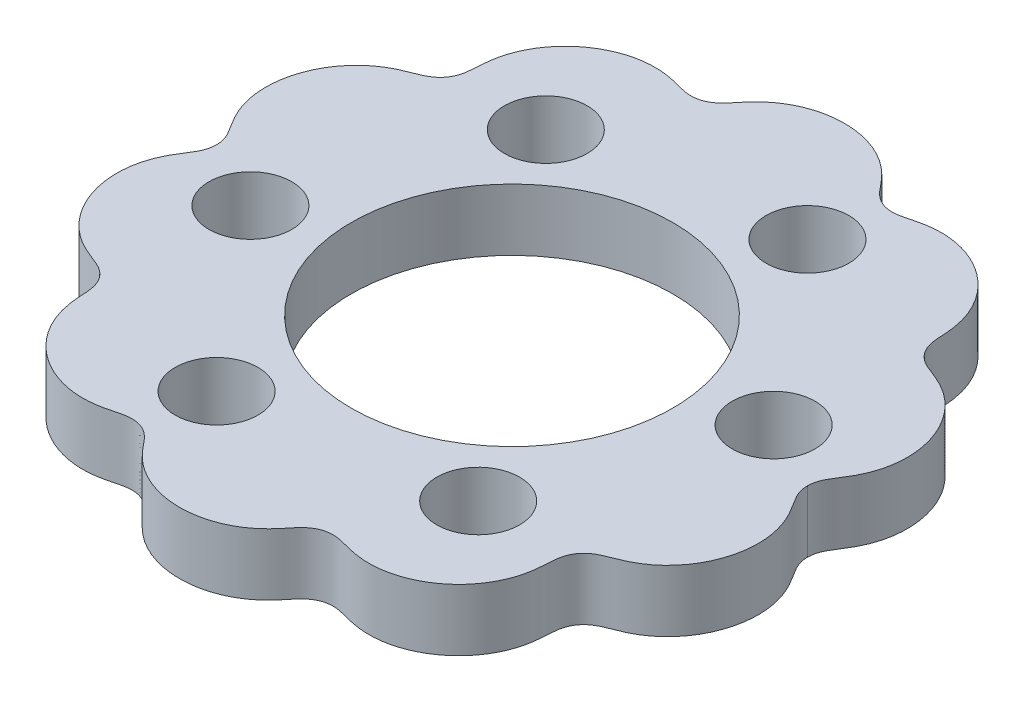
SolidWorks part; units mm, degrees
ref_plane "Front Plane" through (0, 0, 0) normal (0, 0, 1) x (1, 0, 0)
ref_plane "Top Plane" through (0, 0, 0) normal (0, 1, 0) x (1, 0, 0)
ref_plane "Right Plane" through (0, 0, 0) normal (1, 0, 0) x (0, 0, -1)
sketch "Sketch1" plane through (0, 0, 0) normal (0, 1, 0) x (1, 0, 0)
  spline S0 degree 4 poles (25.7906, 7.5343) (25.8788, 7.1133) (25.9899, 6.258) (25.9622, 5.173) (25.6669, 3.909) (25.2966, 3.0278) (25.0022, 2.4855) (24.7411, 2.0653) (24.5631, 1.7918) (24.4128, 1.5559) (24.2753, 1.3229) (24.1728, 1.1289) (24.0852, 0.9325) (24.0168, 0.7401) (23.9736, 0.5903) (23.9409, 0.4443) (23.918, 0.3017) (23.9061, 0.188) (23.9012, 0.082) (23.8998, 0.0096) (23.9001, -0.0378) (23.9031, -0.1354) (23.9124, -0.2583) (23.931, -0.3897) (23.9595, -0.5322) (23.992, -0.6548) (24.033, -0.7865) (24.0838, -0.9249) (24.1521, -1.083) (24.2429, -1.2629) (24.3447, -1.4425) (24.4552, -1.6225) (24.5717, -1.8045) (24.7183, -2.0313) (24.8914, -2.3053) (25.0875, -2.6402) (25.2934, -3.0428) (25.5234, -3.5754) (25.7435, -4.2491) (25.909, -5.0602) (25.989, -6.24) (25.8643, -7.4222) (25.5418, -8.5683) (25.0323, -9.6423) (24.5159, -10.4451) (23.8988, -11.1736) (23.1893, -11.8124) (22.5069, -12.2735) (21.8941, -12.5927) (21.3804, -12.8129) (20.9812, -12.967) (20.5083, -13.1497) (20.0028, -13.3924) (19.5163, -13.7704) (19.1071, -14.3429) (18.9044, -14.9387) (18.8377, -15.5108) (18.8117, -16.0408) (18.7845, -16.4899) (18.7247, -17.0578) (18.5966, -17.7393) (18.287, -18.7429) (17.6345, -19.995) (16.5677, -21.2689) (15.0187, -22.3804) (13.232, -23.0712) (11.6863, -23.2335) (10.5209, -23.1072) (9.745, -22.9271) (9.3314, -22.8175) (8.8415, -22.6876) (8.2891, -22.5904) (7.675, -22.6156) (7.014, -22.8425) (6.5078, -23.2036) (6.1238, -23.6204) (5.7973, -24.0261) (5.517, -24.3664) (4.9887, -24.958) (4.1217, -25.7163) (2.8002, -26.4589) (0.9866, -26.9323) (-0.8925, -26.9446) (-2.4927, -26.549) (-3.7586, -25.9235) (-4.6012, -25.2962) (-5.1069, -24.8217) (-5.4903, -24.3984) (-5.7768, -24.0514) (-6.1092, -23.6377) (-6.4971, -23.212) (-7.008, -22.8447) (-7.6734, -22.6157) (-8.2891, -22.5904) (-8.8414, -22.6876) (-9.3314, -22.8175) (-9.745, -22.9271) (-10.5209, -23.1072) (-11.6863, -23.2335) (-13.232, -23.0712) (-15.0187, -22.3804) (-16.5677, -21.2689) (-17.6345, -19.995) (-18.287, -18.7429) (-18.5966, -17.7393) (-18.7247, -17.0578) (-18.7845, -16.4899) (-18.8117, -16.0408) (-18.8377, -15.5108) (-18.9044, -14.9387) (-19.1071, -14.3429) (-19.5163, -13.7704) (-20.0028, -13.3924) (-20.5083, -13.1497) (-20.9812, -12.967) (-21.3804, -12.8129) (-21.8941, -12.5927) (-22.5069, -12.2735) (-23.1893, -11.8124) (-23.8988, -11.1736) (-24.5159, -10.4451) (-25.0323, -9.6423) (-25.5418, -8.5683) (-25.8643, -7.4222) (-25.989, -6.24) (-25.909, -5.0602) (-25.7435, -4.2491) (-25.5234, -3.5754) (-25.2934, -3.0428) (-25.0875, -2.6402) (-24.8914, -2.3053) (-24.7183, -2.0313) (-24.5717, -1.8045) (-24.4552, -1.6225) (-24.3447, -1.4425) (-24.2429, -1.2629) (-24.1521, -1.083) (-24.0838, -0.9249) (-24.033, -0.7865) (-23.992, -0.6548) (-23.9595, -0.5322) (-23.931, -0.3897) (-23.9124, -0.2583) (-23.9031, -0.1354) (-23.9001, -0.0378) (-23.8998, 0.0096) (-23.9012, 0.082) (-23.9061, 0.188) (-23.918, 0.3017) (-23.9409, 0.4443) (-23.9736, 0.5903) (-24.0168, 0.7401) (-24.0852, 0.9325) (-24.1918, 1.1715) (-24.3429, 1.4455) (-24.5376, 1.7528) (-24.7411, 2.0653) (-25.0022, 2.4855) (-25.2966, 3.0278) (-25.6669, 3.909) (-25.9622, 5.173) (-25.9899, 6.258) (-25.8788, 7.1133) (-25.7906, 7.5343) knots 0 0 0 0 0 0.016557 0.033114 0.041392 0.04967 0.053259 0.056848 0.060437 0.062231 0.064026 0.067263 0.068881 0.0705 0.071881 0.073262 0.074643 0.076024 0.076447 0.07687 0.077627 0.078384 0.079897 0.081411 0.082924 0.083871 0.084817 0.08671 0.088602 0.090495 0.092574 0.094654 0.096734 0.098813 0.102972 0.107132 0.111671 0.11621 0.125289 0.134368 0.143447 0.161605 0.170766 0.179928 0.18909 0.198252 0.207413 0.216574 0.220692 0.22481 0.228927 0.233045 0.240218 0.246328 0.252328 0.259785 0.264113 0.268441 0.27277 0.277098 0.286094 0.29509 0.313082 0.331073 0.349394 0.367716 0.386036 0.390153 0.39427 0.398387 0.402504 0.409677 0.415786 0.421726 0.429063 0.433304 0.437545 0.441787 0.446028 0.463838 0.481648 0.499458 0.517452 0.535446 0.544443 0.55344 0.557769 0.562098 0.566426 0.570755 0.578213 0.584214 0.590323 0.597496 0.601613 0.60573 0.609847 0.613964 0.632284 0.650606 0.668927 0.686918 0.70491 0.713906 0.722902 0.72723 0.731559 0.735887 0.740215 0.747672 0.753672 0.759782 0.766955 0.771073 0.77519 0.779308 0.783426 0.792587 0.801748 0.81091 0.820072 0.829234 0.838395 0.856553 0.865632 0.874711 0.88379 0.888329 0.892868 0.897028 0.901187 0.903266 0.905346 0.907426 0.909505 0.911398 0.91329 0.915183 0.916129 0.917076 0.918589 0.920103 0.921616 0.922373 0.92313 0.923553 0.923976 0.925357 0.926738 0.928119 0.9295 0.931119 0.932737 0.935974 0.939563 0.943152 0.946741 0.95033 0.958608 0.966886 0.983443 1 1 1 1 1 construction
  spline S1 degree 4 poles (23.9, 0) (23.9, -0.0166) (23.9004, -0.0497) (23.9031, -0.1354) (23.9124, -0.2583) (23.931, -0.3897) (23.9595, -0.5322) (23.992, -0.6548) (24.033, -0.7865) (24.0838, -0.9249) (24.1521, -1.083) (24.2429, -1.2629) (24.3447, -1.4425) (24.4552, -1.6225) (24.5717, -1.8045) (24.7183, -2.0313) (24.8914, -2.3053) (25.0875, -2.6402) (25.2934, -3.0428) (25.5234, -3.5754) (25.7435, -4.2491) (25.909, -5.0602) (25.989, -6.24) (25.8643, -7.4222) (25.5418, -8.5683) (25.0323, -9.6423) (24.5159, -10.4451) (23.8988, -11.1736) (23.1893, -11.8124) (22.5069, -12.2735) (21.8941, -12.5927) (21.3804, -12.8129) (20.9812, -12.967) (20.5083, -13.1497) (20.0028, -13.3924) (19.5163, -13.7704) (19.1071, -14.3429) (18.9044, -14.9387) (18.8377, -15.5108) (18.8117, -16.0408) (18.7845, -16.4899) (18.7247, -17.0578) (18.5966, -17.7393) (18.287, -18.7429) (17.6345, -19.995) (16.5677, -21.2689) (15.0187, -22.3804) (13.232, -23.0712) (11.6863, -23.2335) (10.5209, -23.1072) (9.745, -22.9271) (9.3314, -22.8175) (8.8415, -22.6876) (8.2891, -22.5904) (7.675, -22.6156) (7.014, -22.8425) (6.5078, -23.2036) (6.1238, -23.6204) (5.7973, -24.0261) (5.517, -24.3664) (4.9887, -24.958) (4.1217, -25.7163) (2.8002, -26.4589) (0.9866, -26.9323) (-0.8925, -26.9446) (-2.4927, -26.549) (-3.7586, -25.9235) (-4.6012, -25.2962) (-5.1069, -24.8217) (-5.4903, -24.3984) (-5.7768, -24.0514) (-6.1092, -23.6377) (-6.4971, -23.212) (-7.008, -22.8447) (-7.6734, -22.6157) (-8.2891, -22.5904) (-8.8414, -22.6876) (-9.3314, -22.8175) (-9.745, -22.9271) (-10.5209, -23.1072) (-11.6863, -23.2335) (-13.232, -23.0712) (-15.0187, -22.3804) (-16.5677, -21.2689) (-17.6345, -19.995) (-18.287, -18.7429) (-18.5966, -17.7393) (-18.7247, -17.0578) (-18.7845, -16.4899) (-18.8117, -16.0408) (-18.8377, -15.5108) (-18.9044, -14.9387) (-19.1071, -14.3429) (-19.5163, -13.7704) (-20.0028, -13.3924) (-20.5083, -13.1497) (-20.9812, -12.967) (-21.3804, -12.8129) (-21.8941, -12.5927) (-22.5069, -12.2735) (-23.1893, -11.8124) (-23.8988, -11.1736) (-24.5159, -10.4451) (-25.0323, -9.6423) (-25.5418, -8.5683) (-25.8643, -7.4222) (-25.989, -6.24) (-25.909, -5.0602) (-25.7435, -4.2491) (-25.5234, -3.5754) (-25.2934, -3.0428) (-25.0875, -2.6402) (-24.8914, -2.3053) (-24.7183, -2.0313) (-24.5717, -1.8045) (-24.4552, -1.6225) (-24.3447, -1.4425) (-24.2429, -1.2629) (-24.1521, -1.083) (-24.0838, -0.9249) (-24.033, -0.7865) (-23.992, -0.6548) (-23.9595, -0.5322) (-23.931, -0.3897) (-23.9124, -0.2583) (-23.9031, -0.1354) (-23.9004, -0.0497) (-23.9, -0.0166) (-23.9, 0) knots 0.07687 0.07687 0.07687 0.07687 0.07687 0.077627 0.078384 0.079897 0.081411 0.082924 0.083871 0.084817 0.08671 0.088602 0.090495 0.092574 0.094654 0.096734 0.098813 0.102972 0.107132 0.111671 0.11621 0.125289 0.134368 0.143447 0.161605 0.170766 0.179928 0.18909 0.198252 0.207413 0.216574 0.220692 0.22481 0.228927 0.233045 0.240218 0.246328 0.252328 0.259785 0.264113 0.268441 0.27277 0.277098 0.286094 0.29509 0.313082 0.331073 0.349394 0.367716 0.386036 0.390153 0.39427 0.398387 0.402504 0.409677 0.415786 0.421726 0.429063 0.433304 0.437545 0.441787 0.446028 0.463838 0.481648 0.499458 0.517452 0.535446 0.544443 0.55344 0.557769 0.562098 0.566426 0.570755 0.578213 0.584214 0.590323 0.597496 0.601613 0.60573 0.609847 0.613964 0.632284 0.650606 0.668927 0.686918 0.70491 0.713906 0.722902 0.72723 0.731559 0.735887 0.740215 0.747672 0.753672 0.759782 0.766955 0.771073 0.77519 0.779308 0.783426 0.792587 0.801748 0.81091 0.820072 0.829234 0.838395 0.856553 0.865632 0.874711 0.88379 0.888329 0.892868 0.897028 0.901187 0.903266 0.905346 0.907426 0.909505 0.911398 0.91329 0.915183 0.916129 0.917076 0.918589 0.920103 0.921616 0.922373 0.92313 0.92313 0.92313 0.92313 0.92313
  spline S2 degree 4 poles (-25.7906, -7.5343) (-25.8788, -7.1133) (-25.9899, -6.258) (-25.9622, -5.173) (-25.6669, -3.909) (-25.2966, -3.0278) (-25.0022, -2.4855) (-24.7411, -2.0653) (-24.5631, -1.7918) (-24.4128, -1.5559) (-24.2753, -1.3229) (-24.1728, -1.1289) (-24.0852, -0.9325) (-24.0168, -0.7401) (-23.9736, -0.5903) (-23.9409, -0.4443) (-23.918, -0.3017) (-23.9061, -0.188) (-23.9012, -0.082) (-23.8998, -0.0096) (-23.9001, 0.0378) (-23.9031, 0.1354) (-23.9124, 0.2583) (-23.931, 0.3897) (-23.9595, 0.5322) (-23.992, 0.6548) (-24.033, 0.7865) (-24.0838, 0.9249) (-24.1521, 1.083) (-24.2429, 1.2629) (-24.3447, 1.4425) (-24.4552, 1.6225) (-24.5717, 1.8045) (-24.7183, 2.0313) (-24.8914, 2.3053) (-25.0875, 2.6402) (-25.2934, 3.0428) (-25.5234, 3.5754) (-25.7435, 4.2491) (-25.909, 5.0602) (-25.989, 6.24) (-25.8643, 7.4222) (-25.5418, 8.5683) (-25.0323, 9.6423) (-24.5159, 10.4451) (-23.8988, 11.1736) (-23.1893, 11.8124) (-22.5069, 12.2735) (-21.8941, 12.5927) (-21.3804, 12.8129) (-20.9812, 12.967) (-20.5083, 13.1497) (-20.0028, 13.3924) (-19.5163, 13.7704) (-19.1071, 14.3429) (-18.9044, 14.9387) (-18.8377, 15.5108) (-18.8117, 16.0408) (-18.7845, 16.4899) (-18.7247, 17.0578) (-18.5966, 17.7393) (-18.287, 18.7429) (-17.6345, 19.995) (-16.5677, 21.2689) (-15.0187, 22.3804) (-13.232, 23.0712) (-11.6863, 23.2335) (-10.5209, 23.1072) (-9.745, 22.9271) (-9.3314, 22.8175) (-8.8415, 22.6876) (-8.2891, 22.5904) (-7.675, 22.6156) (-7.014, 22.8425) (-6.5078, 23.2036) (-6.1238, 23.6204) (-5.7973, 24.0261) (-5.517, 24.3664) (-4.9887, 24.958) (-4.1217, 25.7163) (-2.8002, 26.4589) (-0.9866, 26.9323) (0.8925, 26.9446) (2.4927, 26.549) (3.7586, 25.9235) (4.6012, 25.2962) (5.1069, 24.8217) (5.4903, 24.3984) (5.7768, 24.0514) (6.1092, 23.6377) (6.4971, 23.212) (7.008, 22.8447) (7.6734, 22.6157) (8.2891, 22.5904) (8.8414, 22.6876) (9.3314, 22.8175) (9.745, 22.9271) (10.5209, 23.1072) (11.6863, 23.2335) (13.232, 23.0712) (15.0187, 22.3804) (16.5677, 21.2689) (17.6345, 19.995) (18.287, 18.7429) (18.5966, 17.7393) (18.7247, 17.0578) (18.7845, 16.4899) (18.8117, 16.0408) (18.8377, 15.5108) (18.9044, 14.9387) (19.1071, 14.3429) (19.5163, 13.7704) (20.0028, 13.3924) (20.5083, 13.1497) (20.9812, 12.967) (21.3804, 12.8129) (21.8941, 12.5927) (22.5069, 12.2735) (23.1893, 11.8124) (23.8988, 11.1736) (24.5159, 10.4451) (25.0323, 9.6423) (25.5418, 8.5683) (25.8643, 7.4222) (25.989, 6.24) (25.909, 5.0602) (25.7435, 4.2491) (25.5234, 3.5754) (25.2934, 3.0428) (25.0875, 2.6402) (24.8914, 2.3053) (24.7183, 2.0313) (24.5717, 1.8045) (24.4552, 1.6225) (24.3447, 1.4425) (24.2429, 1.2629) (24.1521, 1.083) (24.0838, 0.9249) (24.033, 0.7865) (23.992, 0.6547) (23.9595, 0.5322) (23.931, 0.3896) (23.9124, 0.2584) (23.9031, 0.135) (23.8997, 0.0263) (23.8998, -0.0438) (23.905, -0.1791) (23.918, -0.3009) (23.9409, -0.4447) (23.9736, -0.5901) (24.0168, -0.7402) (24.0852, -0.9325) (24.1918, -1.1716) (24.3429, -1.4455) (24.5376, -1.7528) (24.7411, -2.0653) (25.0022, -2.4855) (25.2966, -3.0278) (25.6669, -3.9091) (25.9622, -5.173) (25.9899, -6.258) (25.8788, -7.1133) (25.7906, -7.5343) knots 0 0 0 0 0 0.016557 0.033114 0.041392 0.04967 0.053259 0.056848 0.060437 0.062231 0.064026 0.067263 0.068881 0.0705 0.071881 0.073262 0.074643 0.076024 0.076447 0.07687 0.077627 0.078384 0.079897 0.081411 0.082924 0.083871 0.084817 0.08671 0.088602 0.090495 0.092574 0.094654 0.096734 0.098813 0.102972 0.107132 0.111671 0.11621 0.125289 0.134368 0.143447 0.161605 0.170766 0.179928 0.18909 0.198252 0.207413 0.216574 0.220692 0.22481 0.228927 0.233045 0.240218 0.246328 0.252328 0.259785 0.264113 0.268441 0.27277 0.277098 0.286094 0.29509 0.313082 0.331073 0.349394 0.367716 0.386036 0.390153 0.39427 0.398387 0.402504 0.409677 0.415786 0.421726 0.429063 0.433304 0.437545 0.441787 0.446028 0.463838 0.481648 0.499458 0.517452 0.535446 0.544443 0.55344 0.557769 0.562098 0.566426 0.570755 0.578213 0.584214 0.590323 0.597496 0.601613 0.60573 0.609847 0.613964 0.632284 0.650606 0.668927 0.686918 0.70491 0.713906 0.722902 0.72723 0.731559 0.735887 0.740215 0.747672 0.753672 0.759782 0.766955 0.771073 0.77519 0.779308 0.783426 0.792587 0.801748 0.81091 0.820072 0.829234 0.838395 0.856553 0.865632 0.874711 0.88379 0.888329 0.892868 0.897028 0.901187 0.903266 0.905346 0.907426 0.909505 0.911398 0.91329 0.915183 0.916129 0.917076 0.918589 0.920103 0.921616 0.922373 0.92313 0.923976 0.925357 0.926738 0.928119 0.9295 0.931119 0.932737 0.935974 0.939563 0.943152 0.946741 0.95033 0.958608 0.966886 0.983443 1 1 1 1 1 construction
  spline S3 degree 4 poles (-23.9, 0) (-23.9, 0.0166) (-23.9004, 0.0497) (-23.9031, 0.1354) (-23.9124, 0.2583) (-23.931, 0.3897) (-23.9595, 0.5322) (-23.992, 0.6548) (-24.033, 0.7865) (-24.0838, 0.9249) (-24.1521, 1.083) (-24.2429, 1.2629) (-24.3447, 1.4425) (-24.4552, 1.6225) (-24.5717, 1.8045) (-24.7183, 2.0313) (-24.8914, 2.3053) (-25.0875, 2.6402) (-25.2934, 3.0428) (-25.5234, 3.5754) (-25.7435, 4.2491) (-25.909, 5.0602) (-25.989, 6.24) (-25.8643, 7.4222) (-25.5418, 8.5683) (-25.0323, 9.6423) (-24.5159, 10.4451) (-23.8988, 11.1736) (-23.1893, 11.8124) (-22.5069, 12.2735) (-21.8941, 12.5927) (-21.3804, 12.8129) (-20.9812, 12.967) (-20.5083, 13.1497) (-20.0028, 13.3924) (-19.5163, 13.7704) (-19.1071, 14.3429) (-18.9044, 14.9387) (-18.8377, 15.5108) (-18.8117, 16.0408) (-18.7845, 16.4899) (-18.7247, 17.0578) (-18.5966, 17.7393) (-18.287, 18.7429) (-17.6345, 19.995) (-16.5677, 21.2689) (-15.0187, 22.3804) (-13.232, 23.0712) (-11.6863, 23.2335) (-10.5209, 23.1072) (-9.745, 22.9271) (-9.3314, 22.8175) (-8.8415, 22.6876) (-8.2891, 22.5904) (-7.675, 22.6156) (-7.014, 22.8425) (-6.5078, 23.2036) (-6.1238, 23.6204) (-5.7973, 24.0261) (-5.517, 24.3664) (-4.9887, 24.958) (-4.1217, 25.7163) (-2.8002, 26.4589) (-0.9866, 26.9323) (0.8925, 26.9446) (2.4927, 26.549) (3.7586, 25.9235) (4.6012, 25.2962) (5.1069, 24.8217) (5.4903, 24.3984) (5.7768, 24.0514) (6.1092, 23.6377) (6.4971, 23.212) (7.008, 22.8447) (7.6734, 22.6157) (8.2891, 22.5904) (8.8414, 22.6876) (9.3314, 22.8175) (9.745, 22.9271) (10.5209, 23.1072) (11.6863, 23.2335) (13.232, 23.0712) (15.0187, 22.3804) (16.5677, 21.2689) (17.6345, 19.995) (18.287, 18.7429) (18.5966, 17.7393) (18.7247, 17.0578) (18.7845, 16.4899) (18.8117, 16.0408) (18.8377, 15.5108) (18.9044, 14.9387) (19.1071, 14.3429) (19.5163, 13.7704) (20.0028, 13.3924) (20.5083, 13.1497) (20.9812, 12.967) (21.3804, 12.8129) (21.8941, 12.5927) (22.5069, 12.2735) (23.1893, 11.8124) (23.8988, 11.1736) (24.5159, 10.4451) (25.0323, 9.6423) (25.5418, 8.5683) (25.8643, 7.4222) (25.989, 6.24) (25.909, 5.0602) (25.7435, 4.2491) (25.5234, 3.5754) (25.2934, 3.0428) (25.0875, 2.6402) (24.8914, 2.3053) (24.7183, 2.0313) (24.5717, 1.8045) (24.4552, 1.6225) (24.3447, 1.4425) (24.2429, 1.2629) (24.1521, 1.083) (24.0838, 0.9249) (24.033, 0.7865) (23.992, 0.6547) (23.9595, 0.5322) (23.931, 0.3896) (23.9124, 0.2584) (23.9031, 0.135) (23.9004, 0.0501) (23.9, 0.0166) (23.9, 0) knots 0.07687 0.07687 0.07687 0.07687 0.07687 0.077627 0.078384 0.079897 0.081411 0.082924 0.083871 0.084817 0.08671 0.088602 0.090495 0.092574 0.094654 0.096734 0.098813 0.102972 0.107132 0.111671 0.11621 0.125289 0.134368 0.143447 0.161605 0.170766 0.179928 0.18909 0.198252 0.207413 0.216574 0.220692 0.22481 0.228927 0.233045 0.240218 0.246328 0.252328 0.259785 0.264113 0.268441 0.27277 0.277098 0.286094 0.29509 0.313082 0.331073 0.349394 0.367716 0.386036 0.390153 0.39427 0.398387 0.402504 0.409677 0.415786 0.421726 0.429063 0.433304 0.437545 0.441787 0.446028 0.463838 0.481648 0.499458 0.517452 0.535446 0.544443 0.55344 0.557769 0.562098 0.566426 0.570755 0.578213 0.584214 0.590323 0.597496 0.601613 0.60573 0.609847 0.613964 0.632284 0.650606 0.668927 0.686918 0.70491 0.713906 0.722902 0.72723 0.731559 0.735887 0.740215 0.747672 0.753672 0.759782 0.766955 0.771073 0.77519 0.779308 0.783426 0.792587 0.801748 0.81091 0.820072 0.829234 0.838395 0.856553 0.865632 0.874711 0.88379 0.888329 0.892868 0.897028 0.901187 0.903266 0.905346 0.907426 0.909505 0.911398 0.91329 0.915183 0.916129 0.917076 0.918589 0.920103 0.921616 0.922373 0.92313 0.92313 0.92313 0.92313 0.92313
extrude "Boss-Extrude1" add sketch "Sketch1" along normal blind 5
sketch "Sketch2" plane through (0, 5, 0) normal (0, 1, 0) x (1, 0, 0)
  circle A0 centre (0, 0) radius 13.01
  dimension "D1" = 26.02
extrude "Cut-Extrude1" cut sketch "Sketch2" against normal through all
sketch "Sketch3" plane through (0, 5, 0) normal (0, 1, 0) x (1, 0, 0)
  line L0 (0, 0) -> (33.4644, 0) construction
  line L1 (-55, 0) -> (55, 0) construction
  line L2 (0, 0) -> (18.2722, 2.894) construction
  circle A0 centre (18.2722, 2.894) radius 3.35
  dimension "D3" = 6.7
  dimension "D1" = 9
  dimension "D2" = 18.5
extrude "Cut-Extrude2" cut sketch "Sketch3" against normal through all
pattern_circular "CirPattern1" count 6 over 360 about axis through (0, 0, 0) along (0, 1, 0) of "Cut-Extrude2"
equation "\"pin_circle_R\" = 27"
equation "\"ecc\" = 1.5"
equation "\"n_pins\" = 11"
equation "\"pin_d\" = 3"
equation "\"out_pin_R\" = 18.5"
equation "\"disc_clr\" = 0.1"
equation "\"seat_6803\" = 26.02"
equation "\"disc_t\" = 5"
equation "\"D1@Sketch2\"=\"seat_6803\""
equation "\"D2@Sketch3\"=\"out_pin_R\""
equation "\"D3@Sketch3\"=\"pin_d\" + 2*\"ecc\" + \"out_hole_clr\""
equation "\"out_hole_clr\" = 0.7"
equation "\"seat_6806\" = 42.1"
equation "\"boss_17\" = 17.15"
equation "\"rotor_bolt_R\" = 10"
equation "\"m25_clr\" = 2.8"
equation "\"m25_head\" = 5"
equation "\"insert_hole\" = 4.4"
equation "\"csk\" = 0.6"
equation "\"peg_d\" = 3.0"
equation "\"plug_d\" = 8.6"
equation "\"peg_clr\" = 0.3"
equation "\"m3_clr\" = 3.4"
equation "\"m3_head\" = 6.2"
equation "\"pin_press\" = 3.2"
equation "\"pin_slip\" = 3.35"
equation "\"hub_30\" = 30.20"
equation "\"hub_short\" = 0.2"
equation "\"m3_tap\" = 2.8"
equation "\"rear_plate_t\" = 2"
